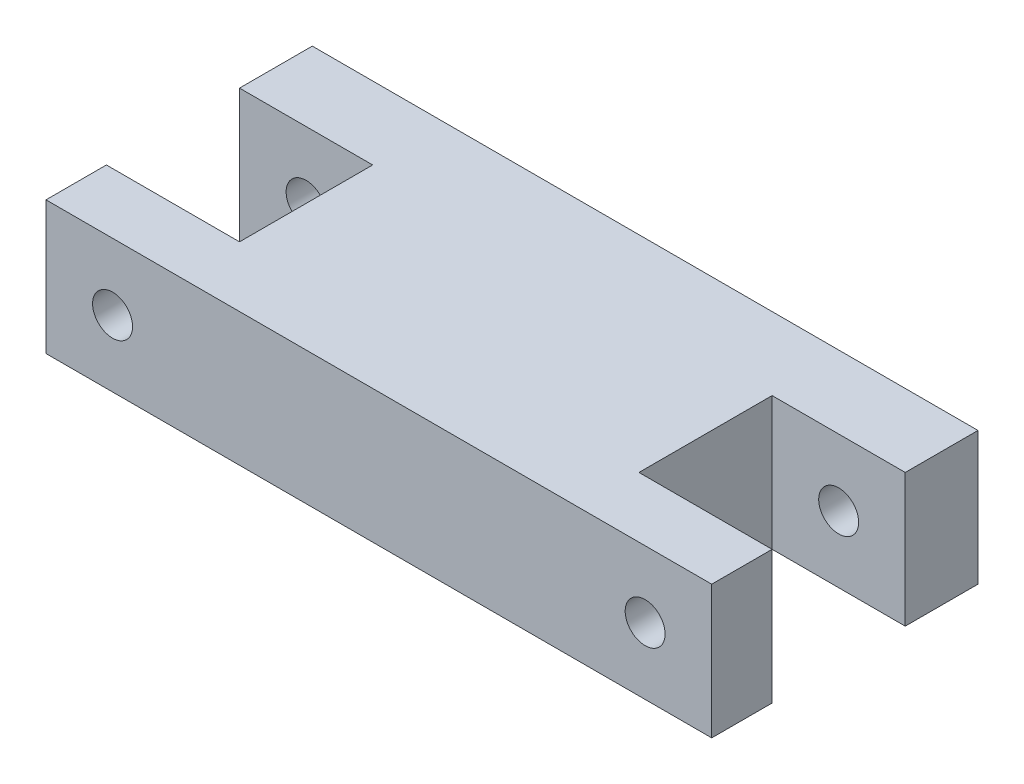
SolidWorks part; units mm, degrees
ref_plane "前视基准面" through (0, 0, 0) normal (0, 0, 1) x (1, 0, 0)
ref_plane "上视基准面" through (0, 0, 0) normal (0, 1, 0) x (1, 0, 0)
ref_plane "右视基准面" through (0, 0, 0) normal (1, 0, 0) x (0, 0, -1)
other "Configuration Table"
sketch "草图1" plane through (0, 0, 0) normal (0, 0, 1) x (1, 0, 0)
  line L1 (-50, 10) -> (50, 10)
  line L2 (-50, 10) -> (-50, -10)
  line L3 (-50, -10) -> (50, -10)
  line L4 (50, 10) -> (50, -10)
  line L5 (-50, 10) -> (50, -10) construction
  line L6 (-50, -10) -> (50, 10) construction
  point P0 (0, 0)
  dimension "D1" = 100
  dimension "D2" = 20
extrude "凸台-拉伸1" add sketch "草图1" along normal blind 40
sketch "草图2" plane through (0, 10, 0) normal (0, 1, 0) x (1, 0, 0)
  line L0 (50, -10.9285) -> (50, -20.9285)
  line L1 (50, -40) -> (50, 0) construction
  line L2 (50, -20.9285) -> (50, -30.9285)
  line L3 (50, -10.9285) -> (30, -10.9285)
  line L4 (50, -30.9285) -> (30, -30.9285)
  line L5 (30, -30.9285) -> (30, -10.9285)
  dimension "D1" = 20
extrude "切除-拉伸1" cut sketch "草图2" against normal through all
mirror "镜向1" about plane through (0, 0, 0) normal (1, 0, 0) of "切除-拉伸1"
ref_point "点2"
sketch "草图4" plane through (0, 0, 10.9285) normal (0, 0, 1) x (1, 0, 0)
  circle A0 centre (40, 0) radius 3
extrude "切除-拉伸2" cut sketch "草图4" against normal through all
mirror "镜向2" about plane through (0, 0, 0) normal (1, 0, 0) of "切除-拉伸2"
ref_plane "基准面1" through (0, 0, 20) normal (0, 0, 1) x (1, 0, 0)
mirror "镜向3" about plane through (0, 0, 20) normal (0, 0, 1) of "镜向2", "切除-拉伸2"
